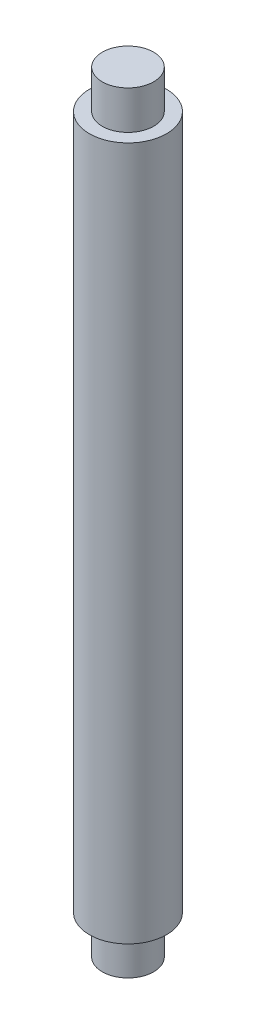
SolidWorks part; units mm, degrees
ref_plane "正面" through (0, 0, 0) normal (0, 0, 1) x (1, 0, 0)
ref_plane "平面" through (0, 0, 0) normal (0, 1, 0) x (1, 0, 0)
ref_plane "右側面" through (0, 0, 0) normal (1, 0, 0) x (0, 0, -1)
sketch "ｽｹｯﾁ1" plane through (0, 0, 0) normal (1, 0, 0) x (0, 0, -1)
  line L0 (16.629, 37.8062) -> (16.629, -22.1938)
  line L1 (16.629, 37.8062) -> (18.629, 37.8062)
  line L2 (18.629, 37.8062) -> (18.629, 34.8062)
  line L3 (18.629, 34.8062) -> (19.629, 34.8062)
  line L6 (18.629, -22.1938) -> (18.629, -19.1938)
  line L7 (18.629, -19.1938) -> (19.629, -19.1938)
  line L8 (16.629, -22.1938) -> (18.629, -22.1938)
  line L9 (19.629, 34.8062) -> (19.629, -19.1938)
revolve "回転1" add sketch "ｽｹｯﾁ1" angle 360 about L0
